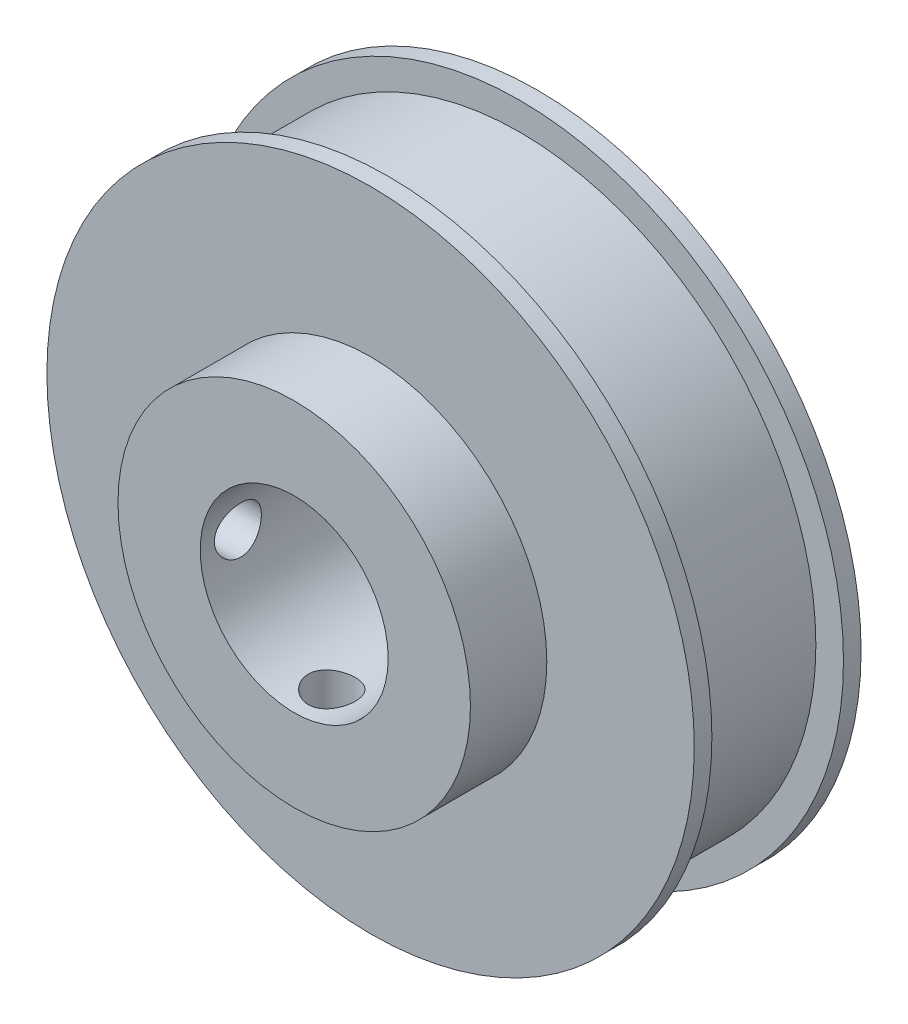
SolidWorks part; units mm, degrees
ref_plane "Alzado" through (0, 0, 0) normal (0, 0, 1) x (1, 0, 0)
ref_plane "Planta" through (0, 0, 0) normal (0, 1, 0) x (1, 0, 0)
ref_plane "Vista lateral" through (0, 0, 0) normal (1, 0, 0) x (0, 0, -1)
sketch "Croquis1" plane through (0, 0, 0) normal (0, 0, 1) x (1, 0, 0)
  circle A0 centre (0, 0) radius 27.55
  dimension "D1" = 55.1
extrude "Saliente-Extruir1" add sketch "Croquis1" along normal blind 1.5
sketch "Croquis2" plane through (0, 0, 1.5) normal (0, 0, 1) x (1, 0, 0)
  circle A0 centre (0, 0) radius 25.2
  dimension "D1" = 50.4
extrude "Saliente-Extruir2" add sketch "Croquis2" along normal blind 11.2
sketch "Croquis3" plane through (0, 0, 12.7) normal (0, 0, 1) x (1, 0, 0)
  circle A0 centre (0, 0) radius 27.55
  dimension "D1" = 55.1
extrude "Saliente-Extruir3" add sketch "Croquis3" along normal blind 1.5
sketch "Croquis8" plane through (0, 0, 14.2) normal (0, 0, 1) x (1, 0, 0)
  circle A0 centre (0, 0) radius 15
  dimension "D1" = 30
extrude "Saliente-Extruir5" add sketch "Croquis8" along normal blind 6.5
sketch "Croquis6" plane through (0, 0, 0) normal (0, 1, 0) x (1, 0, 0)
  line L0 (0, 0) -> (0, -17.5) construction
  circle A0 centre (0, -17.5) radius 2
  dimension "D2" = 4
  dimension "D1" = 17.5
extrude "Cortar-Extruir3" cut sketch "Croquis6" against normal through all
sketch "Croquis5" plane through (0, 0, 0) normal (1, 0, 0) x (0, 0, -1)
  line L0 (0, 0) -> (-17.5, 0) construction
  circle A0 centre (-17.5, 0) radius 2
  dimension "D2" = 4
  dimension "D1" = 17.5
extrude "Cortar-Extruir2" cut sketch "Croquis5" against normal through all
sketch "Croquis4" plane through (0, 0, 20.7) normal (0, 0, 1) x (1, 0, 0)
  circle A0 centre (0, 0) radius 8
  dimension "D1" = 16
extrude "Cortar-Extruir1" cut sketch "Croquis4" against normal through all
